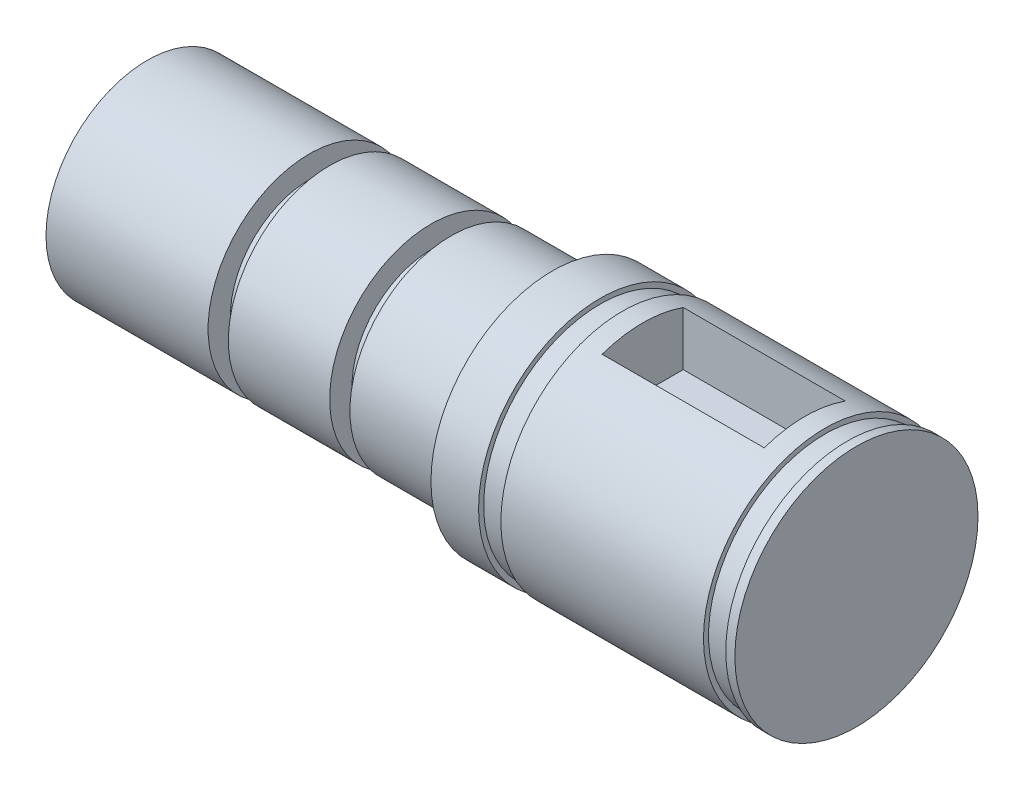
SolidWorks part; units mm, degrees
ref_plane "Front Plane" through (0, 0, 0) normal (0, 0, 1) x (1, 0, 0)
ref_plane "Top Plane" through (0, 0, 0) normal (0, 1, 0) x (1, 0, 0)
ref_plane "Right Plane" through (0, 0, 0) normal (1, 0, 0) x (0, 0, -1)
sketch "Sketch1" plane through (0, 0, 0) normal (1, 0, 0) x (0, 0, -1)
  circle A0 centre (0, 0) radius 6
  dimension "D1" = 12
extrude "Boss-Extrude1" add sketch "Sketch1" along normal blind 15
sketch "Sketch2" plane through (0, 0, 0) normal (-1, 0, 0) x (0, 0, 1)
  circle A0 centre (0, 0) radius 5
  dimension "D1" = 10
extrude "Boss-Extrude2" add sketch "Sketch2" along normal blind 20
ref_plane "Plane1" through (0, 6, 0) normal (0, 1, 0) x (1, 0, 0)
sketch "Sketch3" plane through (0, 6, 0) normal (0, 1, 0) x (1, 0, 0)
  line L0 (15, 0) -> (0, 0) construction
  line L1 (15, -6) -> (15, 6) construction
  line L3 (4.45, -2) -> (12.45, -2)
  line L4 (4.45, -2) -> (4.45, 2)
  line L5 (4.45, 2) -> (12.45, 2)
  line L6 (12.45, -2) -> (12.45, 2)
  line L7 (4.45, -2) -> (12.45, 2) construction
  line L8 (4.45, 2) -> (12.45, -2) construction
  point P5 (8.45, 0)
  point P12 (7.5, 0)
  dimension "D1" = 8
  dimension "D2" = 4
  dimension "D3" = 0.95
extrude "Cut-Extrude1" cut sketch "Sketch3" against normal blind 3
sketch "Sketch4" plane through (0, 0, 0) normal (0, 0, 1) x (1, 0, 0)
  line L0 (-5, 5) -> (-6, 5)
  line L1 (0, 5) -> (-20, 5) construction
  line L2 (-6, 5) -> (-6, 3.9)
  line L3 (-6, 3.9) -> (-5, 3.9)
  line L4 (-5, 3.9) -> (-5, 5)
  line L5 (0, 0) -> (-8.308, 0) construction
  line L6 (0, 5) -> (0, -5) construction
  line L7 (8.45, 5.6569) -> (8.45, 8.5194) construction
  line L8 (-11, 5) -> (-12, 5)
  line L9 (-11, 5) -> (-11, 3.9)
  line L10 (-11, 3.9) -> (-12, 3.9)
  line L11 (-12, 5) -> (-12, 3.9)
  line L12 (2.35, 6) -> (3.45, 6)
  line L13 (4.45, 6) -> (0, 6) construction
  line L14 (3.45, 6) -> (3.45, 5.75)
  line L15 (3.45, 5.75) -> (2.35, 5.75)
  line L16 (2.35, 5.75) -> (2.35, 6)
  line L17 (12.45, 5.6569) -> (4.45, 5.6569) construction
  line L18 (13.45, 6) -> (13.45, 5.75)
  line L19 (14.55, 6) -> (13.45, 6)
  line L20 (14.55, 5.75) -> (14.55, 6)
  line L21 (13.45, 5.75) -> (14.55, 5.75)
  dimension "D1" = 3.9
  dimension "D2" = 1
  dimension "D3" = 5
  dimension "D4" = 3.9
  dimension "D5" = 1
  dimension "D6" = 7
  dimension "groovediameter" = 5.75
  dimension "groovewidth" = 1.1
  dimension "D7" = 1
revolve "Cut-Revolve1" cut sketch "Sketch4" angle 360 about L5
equation "\"shaft-diameter\" =20mm"
equation "\"key-length\"=12mm"
equation "\"key-width\"=4mm"
equation "\"flippershaft-wormgear-diameter\" = 35mm"
equation "\"shaft-ring-groove-depth\"=0.5mm"
equation "\"shaft-ring-groove-width\" = 1.3mm"
equation "\"mini-shaft-diameter\" = 12mm"
equation "\"D1@Sketch1\"=\"mini-shaft-diameter\""
equation "\"D1@Sketch2\"=\"mini-shaft-diameter\"-2"
equation "\"D2@Sketch3\"=\"key-width\""
equation "\"mini-flipper-shaft-diameter\"= 26mm"
equation "\"mini-shaft-ring-groove-diam\"= 7.8mm"
equation "\"mini-shaft-ring-groove-width\"= 1mm"
equation "\"D1@Sketch4\"=\"mini-shaft-ring-groove-diam\"/2"
equation "\"D2@Sketch4\"=\"mini-shaft-ring-groove-width\""
equation "\"D4@Sketch4\"=\"mini-shaft-ring-groove-diam\"/2"
equation "\"D5@Sketch4\"=\"mini-shaft-ring-groove-width\""
